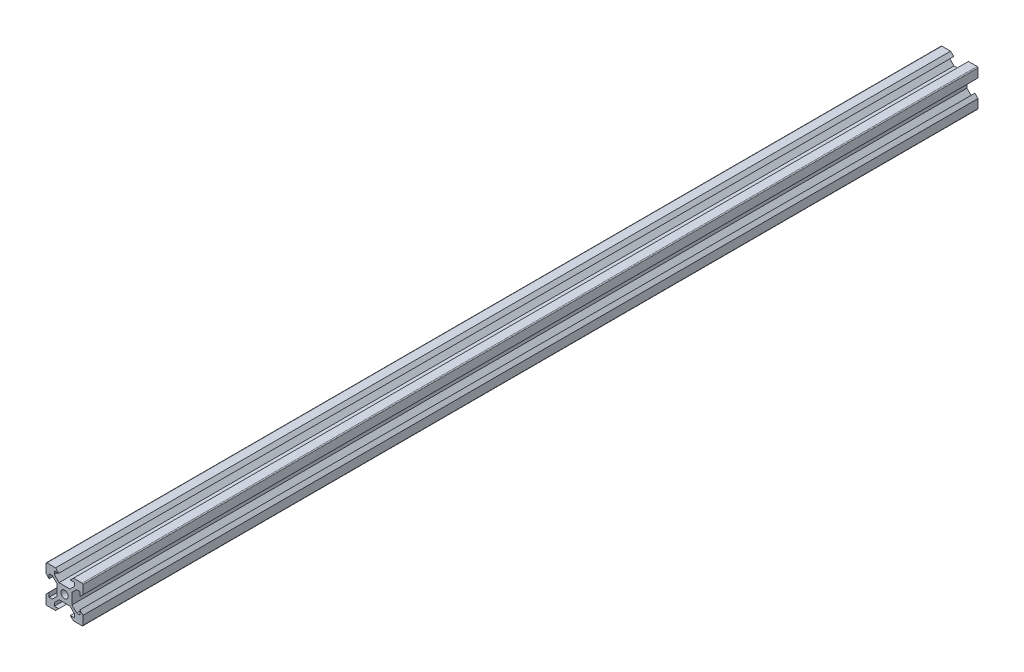
SolidWorks part; units mm, degrees
ref_plane "Alzado" through (0, 0, 0) normal (0, 0, 1) x (1, 0, 0)
ref_plane "Planta" through (0, 0, 0) normal (0, 1, 0) x (1, 0, 0)
ref_plane "Vista lateral" through (0, 0, 0) normal (1, 0, 0) x (0, 0, -1)
sketch "Croquis1" plane through (0, 0, 0) normal (0, 0, 1) x (1, 0, 0)
  line L0 (-4.825, 10) -> (-3.125, 8.3)
  line L1 (-9.5, -10) -> (-4.825, -10)
  line L2 (-10, -9.5) -> (-10, -4.825)
  line L3 (-9.5, 10) -> (-4.825, 10)
  line L4 (10, -9.5) -> (10, -4.825)
  line L5 (-10, -10) -> (10, 10) construction
  line L6 (-10, 10) -> (10, -10) construction
  line L7 (-2.9393, -4) -> (2.9393, -4)
  line L8 (-4, -2.9393) -> (-4, 2.9393)
  line L9 (-2.9393, 4) -> (2.9393, 4)
  line L10 (4, -2.9393) -> (4, 2.9393)
  line L11 (-4, -4) -> (4, 4) construction
  line L12 (-4, 4) -> (4, -4) construction
  line L13 (0, 10) -> (0, -10) construction
  line L14 (-3.125, 8.3) -> (-5.5, 8.3)
  line L15 (-6.5607, 5.5) -> (-4, 2.9393)
  line L16 (-5.5, 6.5607) -> (-2.9393, 4)
  line L17 (-9.4697, 10.5303) -> (10.5303, -9.4697) construction
  line L18 (-10, 4.825) -> (-8.3, 3.125)
  line L19 (-5.5, 8.3) -> (-5.5, 6.5607)
  line L20 (-8.3, 3.125) -> (-8.3, 5.5)
  line L21 (-8.3, 5.5) -> (-6.5607, 5.5)
  line L22 (10, 4.825) -> (8.3, 3.125)
  line L23 (8.3, 3.125) -> (8.3, 5.5)
  line L24 (8.3, 5.5) -> (6.5607, 5.5)
  line L25 (6.5607, 5.5) -> (4, 2.9393)
  line L26 (5.5, 6.5607) -> (2.9393, 4)
  line L27 (5.5, 8.3) -> (5.5, 6.5607)
  line L28 (3.125, 8.3) -> (5.5, 8.3)
  line L29 (4.825, 10) -> (3.125, 8.3)
  line L30 (4.825, -10) -> (3.125, -8.3)
  line L31 (3.125, -8.3) -> (5.5, -8.3)
  line L32 (5.5, -8.3) -> (5.5, -6.5607)
  line L33 (5.5, -6.5607) -> (2.9393, -4)
  line L34 (6.5607, -5.5) -> (4, -2.9393)
  line L35 (8.3, -5.5) -> (6.5607, -5.5)
  line L36 (8.3, -3.125) -> (8.3, -5.5)
  line L37 (10, -4.825) -> (8.3, -3.125)
  line L38 (-10, -4.825) -> (-8.3, -3.125)
  line L39 (-8.3, -3.125) -> (-8.3, -5.5)
  line L40 (-8.3, -5.5) -> (-6.5607, -5.5)
  line L41 (-6.5607, -5.5) -> (-4, -2.9393)
  line L42 (-5.5, -6.5607) -> (-2.9393, -4)
  line L43 (-5.5, -8.3) -> (-5.5, -6.5607)
  line L44 (-3.125, -8.3) -> (-5.5, -8.3)
  line L45 (-4.825, -10) -> (-3.125, -8.3)
  line L46 (-10, 4.825) -> (-10, 9.5)
  line L47 (4.825, 10) -> (9.5, 10)
  line L48 (10, 4.825) -> (10, 9.5)
  line L49 (4.825, -10) -> (9.5, -10)
  circle A0 centre (0, 0) radius 2
  arc A1 (-10, 9.5) -> (-9.5, 10) centre (-9.5, 9.5) cw
  arc A2 (9.5, 10) -> (10, 9.5) centre (9.5, 9.5) cw
  arc A3 (9.5, -10) -> (10, -9.5) centre (9.5, -9.5) ccw
  arc A4 (-9.5, -10) -> (-10, -9.5) centre (-9.5, -9.5) cw
  point P0 (0, 0)
  point P59 (0, 0)
  dimension "D2" = 4
  dimension "D9" = 0.5
  dimension "D1" = 20
  dimension "D3" = 8
  dimension "D4" = 3.125
  dimension "D5" = 5.5
  dimension "D6" = 4.3
  dimension "D7" = 4
  dimension "D8" = 0.75
extrude "Saliente-Extruir2" add sketch "Croquis1" along normal mid plane 484
